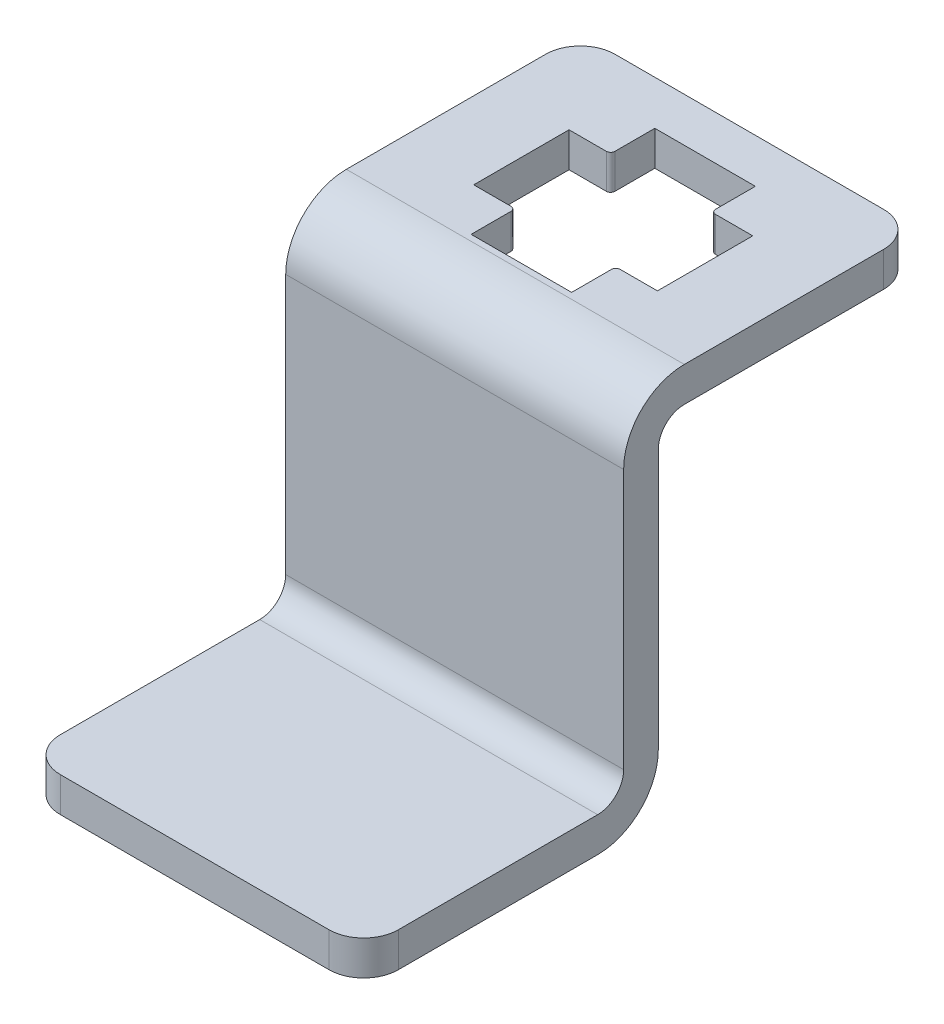
SolidWorks part; units mm, degrees
ref_plane "Front Plane" through (0, 0, 0) normal (0, 0, 1) x (1, 0, 0)
ref_plane "Top Plane" through (0, 0, 0) normal (0, 1, 0) x (1, 0, 0)
ref_plane "Right Plane" through (0, 0, 0) normal (1, 0, 0) x (0, 0, -1)
sketch "Sketch1" plane through (0, 0, 0) normal (1, 0, 0) x (0, 0, -1)
  line L0 (0, 0) -> (15, 0)
  line L1 (15, 0) -> (15, 20)
  line L2 (15, 20) -> (32, 20)
  dimension "D1" = 17
  dimension "D2" = 32
  dimension "D3" = 20
extrude "Extrude-Thin1" add sketch "Sketch1" along normal mid plane 19.5 thin
sketch "Sketch3" [suppressed] plane through (0, 0, 0) normal (1, 0, 0) x (0, 0, -1)
  line L0 (0, 0) -> (18, 0)
  line L1 (18, 0) -> (18, 12)
  line L2 (18, 12) -> (42, 12)
  dimension "D1" = 24
  dimension "D2" = 18
  dimension "D3" = 12
sketch "Sketch4" [suppressed] plane through (0, 0, 0) normal (0, 0, 1) x (1, 0, 0)
  line L0 (10, 0) -> (-10, 0)
  line L1 (-10, 0) -> (-10, 2)
  line L2 (-10, 2) -> (10, 2)
  line L3 (10, 2) -> (10, 0)
  dimension "D1" = 20
  dimension "D2" = 2
ref_plane "Plane1" [suppressed] through (0, 0, -18) normal (0, 0, 1) x (1, 0, 0)
ref_plane "Plane2" [suppressed] through (0, 0, -42) normal (0, 0, 1) x (1, 0, 0)
ref_plane "Plane3" [suppressed] through (0, 0, -16) normal (0, 0, 1) x (1, 0, 0)
sketch "Sketch5" [suppressed] plane through (0, 0, -16) normal (0, 0, 1) x (1, 0, 0)
  line L0 (10, 0) -> (-10, 0)
  line L1 (-10, 0) -> (-10, 2)
  line L2 (-10, 2) -> (10, 2)
  line L3 (10, 2) -> (10, 0)
  dimension "D1" = 20
  dimension "D2" = 2
sketch "Sketch7" [suppressed] plane through (0, 0, -18) normal (0, 0, 1) x (1, 0, 0)
  line L0 (5, 12) -> (-5, 12)
  line L1 (-5, 12) -> (-5, 14)
  line L2 (-5, 14) -> (5, 14)
  line L3 (5, 14) -> (5, 12)
  dimension "D1" = 10
  dimension "D2" = 2
sketch "Sketch6" [suppressed] plane through (0, 0, -42) normal (0, 0, 1) x (1, 0, 0)
  line L0 (5, 12) -> (-5, 12)
  line L1 (-5, 12) -> (-5, 14)
  line L2 (-5, 14) -> (5, 14)
  line L3 (5, 14) -> (5, 12)
  dimension "D1" = 10
  dimension "D2" = 2
sketch "Sketch2" plane through (0, 20, 0) normal (0, 1, 0) x (1, 0, 0)
  line L0 (-2.9, 29.45) -> (2.9, 29.45)
  line L1 (-2.9, 29.45) -> (-2.9, 27.15)
  line L2 (-3.15, 26.9) -> (-5.3, 26.9)
  line L3 (-5.3, 26.9) -> (-5.3, 21.4)
  line L4 (0, 40.7705) -> (0, 24.15) construction
  line L5 (-6.8365, 24.15) -> (8.4937, 24.15) construction
  line L6 (9.75, 32) -> (-9.75, 32) construction
  line L10 (2.9, -36.95) -> (5.3, -36.95)
  line L11 (5.3, -36.95) -> (5.3, -31.45)
  line L12 (2.9, -39.5) -> (2.9, -36.95)
  line L13 (2.9, -39.5) -> (-2.9, -39.5)
  line L14 (-36.95, -2.9) -> (-36.95, -5.3)
  line L15 (-36.95, -5.3) -> (-31.45, -5.3)
  line L16 (-39.5, -2.9) -> (-36.95, -2.9)
  line L17 (-39.5, -2.9) -> (-39.5, 2.9)
  line L18 (5.3, 26.9) -> (5.3, 21.4)
  line L19 (3.15, 26.9) -> (5.3, 26.9)
  line L20 (2.9, 29.45) -> (2.9, 27.15)
  line L21 (-3.15, 21.4) -> (-5.3, 21.4)
  line L22 (-2.9, 18.85) -> (-2.9, 21.15)
  line L23 (-2.9, 18.85) -> (2.9, 18.85)
  line L24 (2.9, 18.85) -> (2.9, 21.15)
  line L25 (3.15, 21.4) -> (5.3, 21.4)
  line L29 (0, 15) -> (0, 32) construction
  arc A0 (-3.15, 21.4) -> (-2.9, 21.15) centre (-3.15, 21.15) cw
  arc A1 (2.9, 21.15) -> (3.15, 21.4) centre (3.15, 21.15) cw
  arc A2 (3.15, 26.9) -> (2.9, 27.15) centre (3.15, 27.15) cw
  arc A3 (-2.9, 27.15) -> (-3.15, 26.9) centre (-3.15, 27.15) cw
  point P10 (0, 24.15)
  point P28 (0, 0)
  point P31 (0, 29.45)
  point P32 (-5.3, 24.15)
  point P37 (5.3, 24.15)
  point P39 (-2.9, 21.4)
  point P42 (2.9, 21.4)
  point P45 (2.9, 26.9)
  point P48 (-2.9, 26.9)
  dimension "D6" = 0.25
  dimension "D2" = 10.6
  dimension "D3" = 5.8
  dimension "D4" = 5.5
  dimension "D5" = 10.6
  dimension "D1" = 7.85
extrude "Cut-Extrude1" cut sketch "Sketch2" against normal up to surface (2 mm away) contours L2 L3 L21 A0 L22 L23 L24 A1 L25 L18 L19 A2 L20 L0 L1 A3 up to face at (0, 18, -25.25)
fillet "Fillet1" [suppressed] radius 2
fillet "Fillet2" radius 2 4 edges at (-9.75, -1, 0) (9.75, -1, 0) (9.75, 19, -32) (-9.75, 19, -32)
sketch "Sketch9" plane through (0, 0, 0) normal (0, 1, 0) x (1, 0, 0)
  line L0 (9.75, 13.5) -> (-9.75, 13.5) construction
  line L2 (-5, 13.5) -> (-5, 1.9656)
  line L4 (5, 13.5) -> (5, 1.9656)
  line L5 (7.75, 0) -> (-7.75, 0) construction
  line L6 (9.75, 2) -> (9.75, 13.5) construction
  line L8 (7.75, 0) -> (3.0344, 0)
  line L9 (9.75, 2) -> (9.75, 13.5)
  line L10 (9.75, 13.5) -> (5, 13.5)
  line L14 (-3.0344, 0) -> (3.0344, 0) construction
  line L15 (-9.75, 2) -> (-9.75, 13.5) construction
  line L16 (-9.75, 2) -> (-9.75, 13.5)
  line L17 (-5, 13.5) -> (-9.75, 13.5)
  line L18 (-3.0344, 0) -> (-7.75, 0)
  arc A2 (3.0344, 0) -> (5, 1.9656) centre (3.0344, 1.9656) ccw
  arc A3 (-5, 1.9656) -> (-3.0344, 0) centre (-3.0344, 1.9656) ccw
  arc A5 (7.75, 0) -> (9.75, 2) centre (7.75, 2) ccw construction
  arc A7 (7.75, 0) -> (9.75, 2) centre (7.75, 2) ccw
  arc A8 (-9.75, 2) -> (-7.75, 0) centre (-7.75, 2) ccw construction
  arc A9 (-9.75, 2) -> (-7.75, 0) centre (-7.75, 2) ccw
  point P13 (-5, 13.5)
  point P16 (4.2525, 0)
  dimension "D2" = 10
extrude "Cut-Extrude2" [suppressed] cut sketch "Sketch9" against normal blind 10
fillet "Fillet3" [suppressed] radius 5
fillet "Fillet4" [suppressed] radius 5
